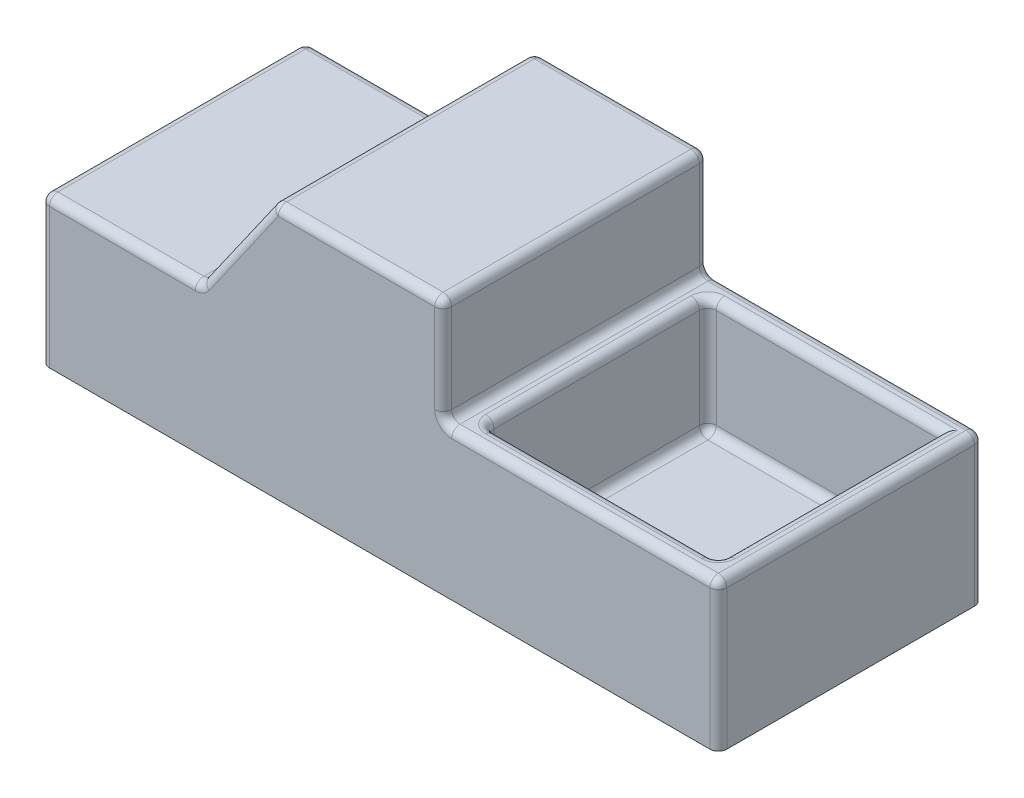
SolidWorks part; units mm, degrees
material "PC High Viscosity"
ref_plane "Front Plane" through (0, 0, 0) normal (0, 0, 1) x (1, 0, 0)
ref_plane "Top Plane" through (0, 0, 0) normal (0, 1, 0) x (1, 0, 0)
ref_plane "Right Plane" through (0, 0, 0) normal (1, 0, 0) x (0, 0, -1)
sketch "Sketch1" plane through (0, 0, 0) normal (0, 0, 1) x (1, 0, 0)
  line L0 (-406.4, 88.9) -> (-406.4, -88.9)
  line L1 (-406.4, -88.9) -> (406.4, -88.9)
  line L2 (406.4, -88.9) -> (406.4, 88.9)
  line L3 (406.4, 88.9) -> (76.2, 88.9)
  line L4 (76.2, 88.9) -> (76.2, 215.9)
  line L5 (76.2, 215.9) -> (-126.9736, 215.9)
  line L6 (-126.9736, 215.9) -> (-215.9, 88.9)
  line L7 (-215.9, 88.9) -> (-406.4, 88.9)
  line L8 (-406.4, 88.9) -> (406.4, -88.9) construction
  line L9 (-406.4, -88.9) -> (406.4, 88.9) construction
  point P2 (0, 0)
  dimension "D1" = 812.8
  dimension "D2" = 190.5
  dimension "D3" = 177.8
  dimension "D4" = 177.8
  dimension "D5" = 330.2
  dimension "D6" = 127
  dimension "D7" = 55
extrude "Boss-Extrude1" add sketch "Sketch1" along normal mid plane 317.5
sketch "Sketch2" plane through (0, 88.9, 0) normal (0, 1, 0) x (1, 0, 0)
  line L0 (0, 0) -> (457.4515, 0) construction
  line L1 (381, -133.35) -> (101.6, -133.35)
  line L2 (381, -133.35) -> (381, 133.35)
  line L3 (381, 133.35) -> (101.6, 133.35)
  line L4 (101.6, -133.35) -> (101.6, 133.35)
  line L5 (381, -133.35) -> (101.6, 133.35) construction
  line L6 (381, 133.35) -> (101.6, -133.35) construction
  line L7 (406.4, 158.75) -> (76.2, 158.75) construction
  line L8 (406.4, -158.75) -> (406.4, 158.75) construction
  line L9 (76.2, -158.75) -> (76.2, 158.75) construction
  line L10 (406.4, -158.75) -> (76.2, -158.75) construction
  point P0 (241.3, 0)
  dimension "D1" = 25.4
  dimension "D2" = 25.4
  dimension "D3" = 25.4
  dimension "D4" = 25.4
extrude "Cut-Extrude1" cut sketch "Sketch2" against normal blind 139.7
fillet "Fillet1" radius 10.16 31 edges at (241.3, 88.9, -133.35) (101.6, 88.9, 0) (381, 88.9, 0) (-171.4368, 152.4, 158.75) (-171.4368, 152.4, -158.75) (101.6, 19.05, 133.35) (381, 19.05, 133.35) (241.3, 88.9, 133.35) (241.3, -50.8, -133.35) (381, -50.8, 0) (241.3, -50.8, 133.35) (101.6, -50.8, 0) (-215.9, 88.9, 0) (-311.15, 88.9, 158.75) (-406.4, 88.9, 0) (-311.15, 88.9, -158.75) (76.2, 88.9, 0) (406.4, 88.9, 0) (406.4, 0, -158.75) (406.4, 0, 158.75) (101.6, 19.05, -133.35) (241.3, 88.9, -158.75) (241.3, 88.9, 158.75) (76.2, 152.4, -158.75) (76.2, 152.4, 158.75) (-25.3868, 215.9, -158.75) (-25.3868, 215.9, 158.75) (76.2, 215.9, 0) (-126.9736, 215.9, 0) (-406.4, 0, -158.75) (-406.4, 0, 158.75)
sketch "Sketch3" plane through (0, -88.9, 0) normal (0, -1, 0) x (1, 0, 0)
  circle A0 centre (0, 0) radius 20
